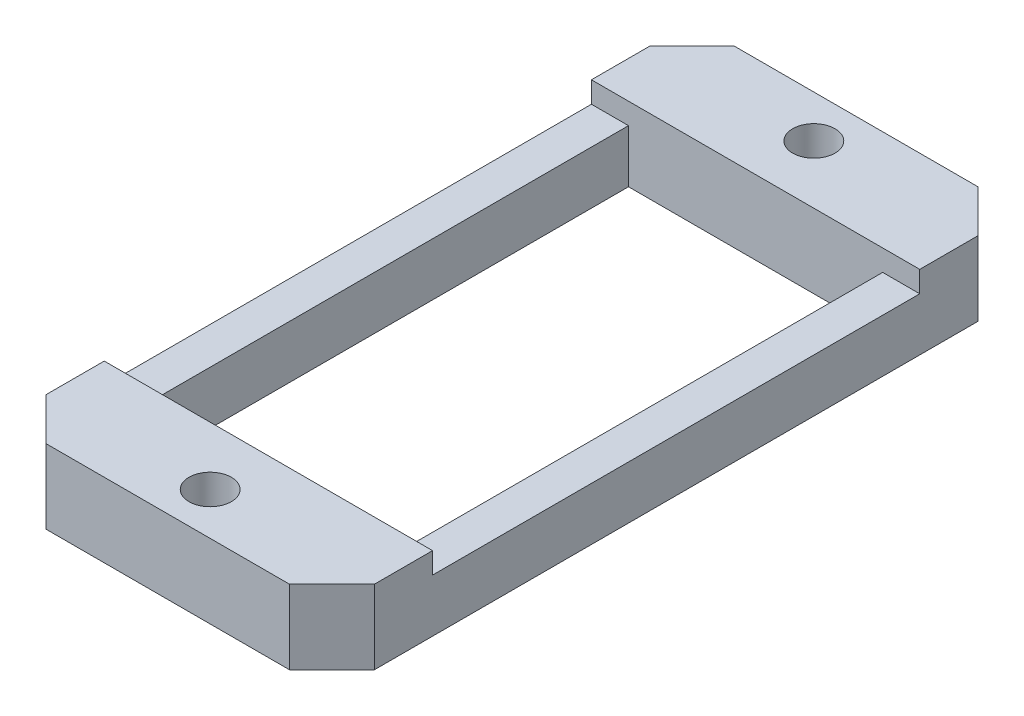
SolidWorks part; units mm, degrees
material "ABS"
ref_plane "前基準面" through (0, 0, 0) normal (0, 0, 1) x (1, 0, 0)
ref_plane "上基準面" through (0, 0, 0) normal (0, 1, 0) x (1, 0, 0)
ref_plane "右基準面" through (0, 0, 0) normal (1, 0, 0) x (0, 0, -1)
sketch "草圖2" plane through (0, 0, 0) normal (1, 0, 0) x (0, 0, -1)
  line L0 (27.75, 3.5) -> (32.5, 3.5)
  line L1 (0, 0) -> (32.5, 0)
  line L2 (0, 0) -> (0, 3.5)
  line L3 (0, 3.5) -> (4.75, 3.5)
  line L4 (32.5, 0) -> (32.5, 3.5)
  line L6 (4.75, 3.5) -> (4.75, 2.5)
  line L7 (4.75, 2.5) -> (27.75, 2.5)
  line L8 (27.75, 3.5) -> (27.75, 2.5)
  dimension "D1" = 32.5
  dimension "D2" = 3.5
  dimension "D3" = 2.5
  dimension "D4" = 23
extrude "填料-伸長1" add sketch "草圖2" along normal mid plane 15.5
sketch "草圖3" plane through (0, 0, 0) normal (0, -1, 0) x (1, 0, 0)
  line L0 (0, 0) -> (0, -32.5) construction
  line L1 (-6, -4.75) -> (6, -4.75)
  line L2 (-6, -4.75) -> (-6, -27.75)
  line L3 (-6, -27.75) -> (6, -27.75)
  line L4 (6, -4.75) -> (6, -27.75)
  line L5 (-6, -4.75) -> (6, -27.75) construction
  line L6 (-6, -27.75) -> (6, -4.75) construction
  line L7 (7.75, 0) -> (-7.75, 0) construction
  line L8 (7.75, -32.5) -> (-7.75, -32.5) construction
  line L9 (0, -2) -> (0, -30.5) construction
  circle A0 centre (0, -2) radius 1
  circle A1 centre (0, -30.5) radius 1
  point P0 (0, -16.25)
  point P15 (0, -16.25)
  dimension "D4" = 2
  dimension "D1" = 12
  dimension "D2" = 23
  dimension "D3" = 28.5
extrude "除料-伸長1" cut sketch "草圖3" against normal through all
chamfer "導角1" distance 2 4 edges at (-7.75, 1.75, 0) (-7.75, 1.75, -32.5) (7.75, 1.75, -32.5) (7.75, 1.75, 0)
